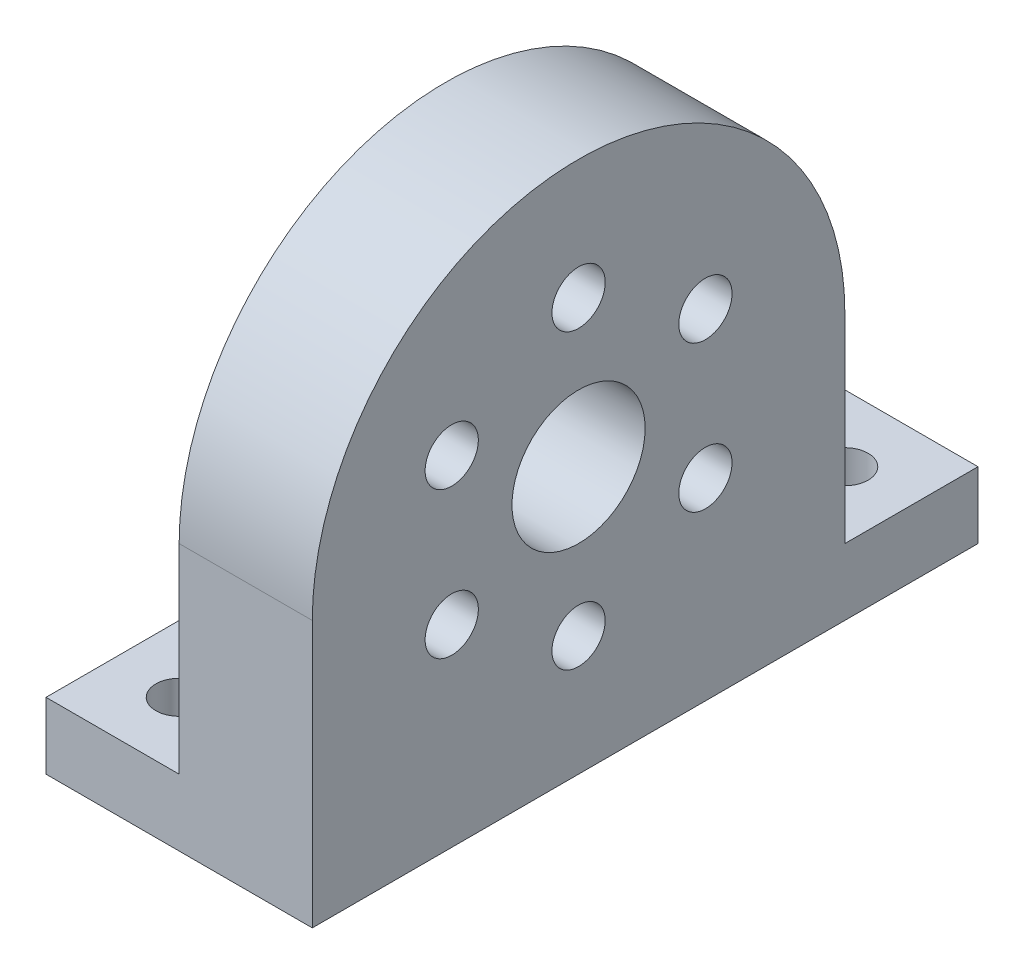
SolidWorks part; units mm, degrees
material "ABS"
ref_plane "Front Plane" through (0, 0, 0) normal (0, 0, 1) x (1, 0, 0)
ref_plane "Top Plane" through (0, 0, 0) normal (0, 1, 0) x (1, 0, 0)
ref_plane "Right Plane" through (0, 0, 0) normal (1, 0, 0) x (0, 0, -1)
sketch "Sketch1" plane through (0, 0, 0) normal (1, 0, 0) x (0, 0, -1)
  line L0 (20, -15) -> (30, -15)
  line L1 (-30, -20) -> (30, -20)
  line L2 (-30, -20) -> (-30, -15)
  line L3 (-30, -15) -> (-20, -15)
  line L4 (30, -20) -> (30, -15)
  line L6 (-20, 0) -> (-20, -15)
  line L7 (-22.3599, -20) -> (-15.8566, -20)
  line L10 (20, 0) -> (20, -15)
  line L11 (17.6401, -20) -> (9.951, -20)
  line L12 (-20, -15) -> (-20, -20)
  circle A1 centre (0, 11) radius 2
  circle A2 centre (9.5263, 5.5) radius 2
  circle A3 centre (9.5263, -5.5) radius 2
  circle A4 centre (0, -11) radius 2
  circle A5 centre (-9.5263, -5.5) radius 2
  circle A6 centre (-9.5263, 5.5) radius 2
  arc A7 (20, 0) -> (-20, 0) centre (0, 0) ccw
  circle A8 centre (0, 0) radius 5
  point P18 (0, 0)
  dimension "D1" = 4
  dimension "D2" = 10
  dimension "D5" = 20
  dimension "D11" = 9.951
  dimension "D3" = 11
  dimension "D6" = 30
  dimension "D7" = 30
  dimension "D8" = 5
  dimension "D9" = 10
  dimension "D10" = 20
  dimension "D12" = 17.6401
  dimension "D13" = 15.8566
  dimension "D14" = 22.3599
  dimension "D4" = 6
extrude "Boss-Extrude1" add sketch "Sketch1" along normal blind 10 contours L10 A7 L6 L3 L2 L1 L4 L0 A8 A1 A2 A3 A4 A5 A6
hole_wizard "CSK for M3 Flat Head Machine Screw1" positions "Sketch3" profile "Sketch4" countersink size "M3" standard "ANSI Metric" end condition through all
sketch "Sketch3" plane through (0, 0, 0) normal (-1, 0, 0) x (0, 0, 1)
  point P0 (0, 11)
  point P3 (9.5263, 5.5)
  point P6 (9.5263, -5.5)
  point P9 (0, -11)
  point P12 (-9.5263, -5.5)
  point P15 (-9.5263, 5.5)
sketch "Sketch4" plane through (0, 11, 0) normal (0, 1, 0) x (0, 0, 1)
  line L0 (0, 0) -> (0, 10)
  line L1 (0, 10) -> (1.7, 10)
  line L2 (1.7, 10) -> (1.7, 1.45)
  line L3 (1.7, 1.45) -> (3.15, 0)
  line L5 (3.15, 0) -> (0, 0)
  line L6 (-1.7, 1.45) -> (-3.15, 0) construction
  line L11 (0, -6.35) -> (0, 107.95) construction
  dimension "Thru Hole Dia." = 3.4
  dimension "Thru Hole Depth" = 10
  dimension "Near C'Sink Dia." = 6.3
  dimension "Near C'Sink Angle" = 90
sketch "Sketch6" plane through (0, -20, 0) normal (0, -1, 0) x (1, 0, 0)
  line L0 (0, 20) -> (-10, 20)
  line L1 (-10, 20) -> (-10, 10)
  line L2 (-10, 10) -> (0, 10)
  line L3 (0, 20) -> (0, -30) construction
  line L4 (0, 20) -> (10, 20)
  line L5 (10, 20) -> (10, 10)
  line L6 (10, 20) -> (10, -30) construction
  line L7 (10, 10) -> (0, 10)
  dimension "D1" = 10
  dimension "D2" = 10
extrude "Boss-Extrude2" add sketch "Sketch6" against normal blind 5
hole_wizard "Ø3.0mm Dowel Hole1" positions "3DSketch1" profile "Sketch7" hole size "Ø3.0" standard "ANSI Metric"
sketch3d "3DSketch1"
  line L5 (0, -15, 20) -> (-10, -15, 20) construction
  line L6 (-10, -15, 20) -> (-10, -15, 10) construction
  line L7 (10, -15, -20) -> (10, -15, -30) construction
  line L8 (10, -15, -30) -> (0, -15, -30) construction
  point P0 (5, -15, -25)
  point P2 (-5, -15, 15)
  dimension "D1" = 5
  dimension "D2" = 5
  dimension "D3" = 5
  dimension "D4" = 5
sketch "Sketch7" plane through (5, -15, -25) normal (1, 0, 0) x (0, 0, 1)
  line L0 (0, 0) -> (0, 5)
  line L1 (0, 5) -> (1.75, 5)
  line L2 (1.75, 5) -> (1.75, 0)
  line L5 (1.75, 0) -> (0, 0)
  line L10 (0, 5) -> (-1.75, 5) construction
  line L11 (0, -6.35) -> (0, 107.95) construction
  dimension "Hole Dia." = 3.5
  dimension "Hole Depth" = 5
  dimension "Drill Angle" = 180
